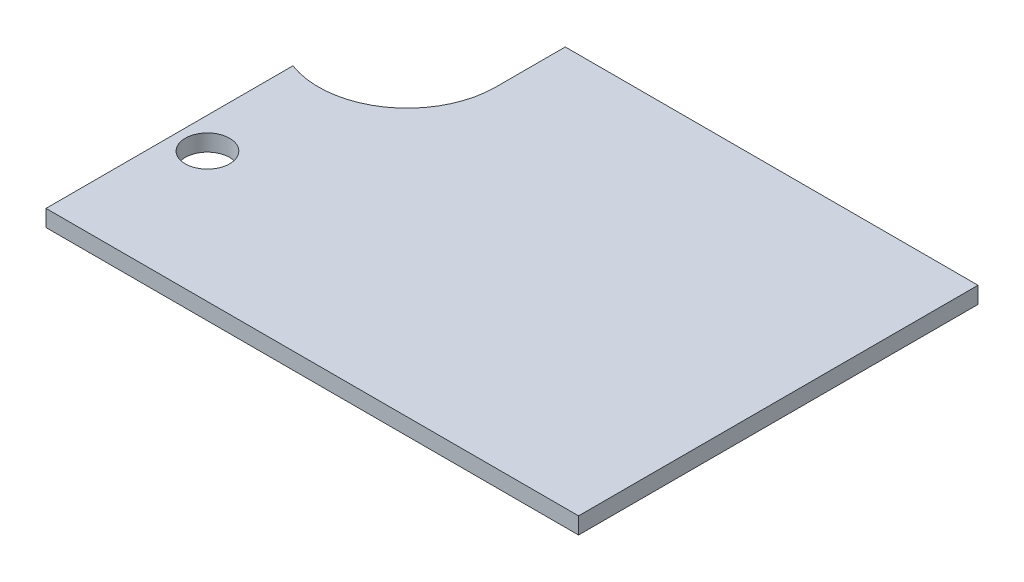
SolidWorks part; units mm, degrees
material "Malleable Cast Iron"
ref_plane "Front Plane" through (0, 0, 0) normal (0, 0, 1) x (1, 0, 0)
ref_plane "Top Plane" through (0, 0, 0) normal (0, 1, 0) x (1, 0, 0)
ref_plane "Right Plane" through (0, 0, 0) normal (1, 0, 0) x (0, 0, -1)
sketch "Sketch1" plane through (0, 0, 0) normal (0, 1, 0) x (1, 0, 0)
  line L0 (-304.8, 228.6) -> (304.8, -228.6) construction
  line L1 (-304.8, 228.6) -> (304.8, 228.6)
  line L2 (-304.8, 228.6) -> (-304.8, -228.6)
  line L3 (-304.8, -228.6) -> (304.8, -228.6)
  line L4 (304.8, 228.6) -> (304.8, -228.6)
  dimension "D1" = 609.6
  dimension "D2" = 457.2
extrude "Boss-Extrude1" add sketch "Sketch1" along normal blind 19.05
sketch "Sketch2" plane through (0, 0, 0) normal (0, -1, 0) x (1, 0, 0)
  circle A0 centre (-269.24, 79.375) radius 25.4
  dimension "D1" = 50.8
extrude "Cut-Extrude1" cut sketch "Sketch2" against normal through all
sketch "Sketch4" plane through (0, 0, 0) normal (0, -1, 0) x (1, 0, 0)
  circle A0 centre (-269.24, -149.225) radius 101.6
  circle A1 centre (-269.24, -149.225) radius 101.6 construction
extrude "Cut-Extrude2" cut sketch "Sketch4" against normal through all
sketch "Sketch6" plane through (0, 19.05, 0) normal (0, 1, 0) x (1, 0, 0)
  line L0 (-304.8, -228.6) -> (-304.8, 54.0512) construction
  line L1 (-167.64, 149.225) -> (-304.8, 149.225)
  line L2 (-167.64, 149.225) -> (-167.64, 228.6)
  line L3 (-167.64, 228.6) -> (-304.8, 228.6)
  line L4 (-304.8, 149.225) -> (-304.8, 228.6)
  line L5 (304.8, 228.6) -> (-205.8194, 228.6) construction
  arc A1 (-304.8, 54.0512) -> (-205.8194, 228.6) centre (-269.24, 149.225) ccw construction
  point P4 (-269.24, 149.225)
extrude "Cut-Extrude3" cut sketch "Sketch6" against normal through all
